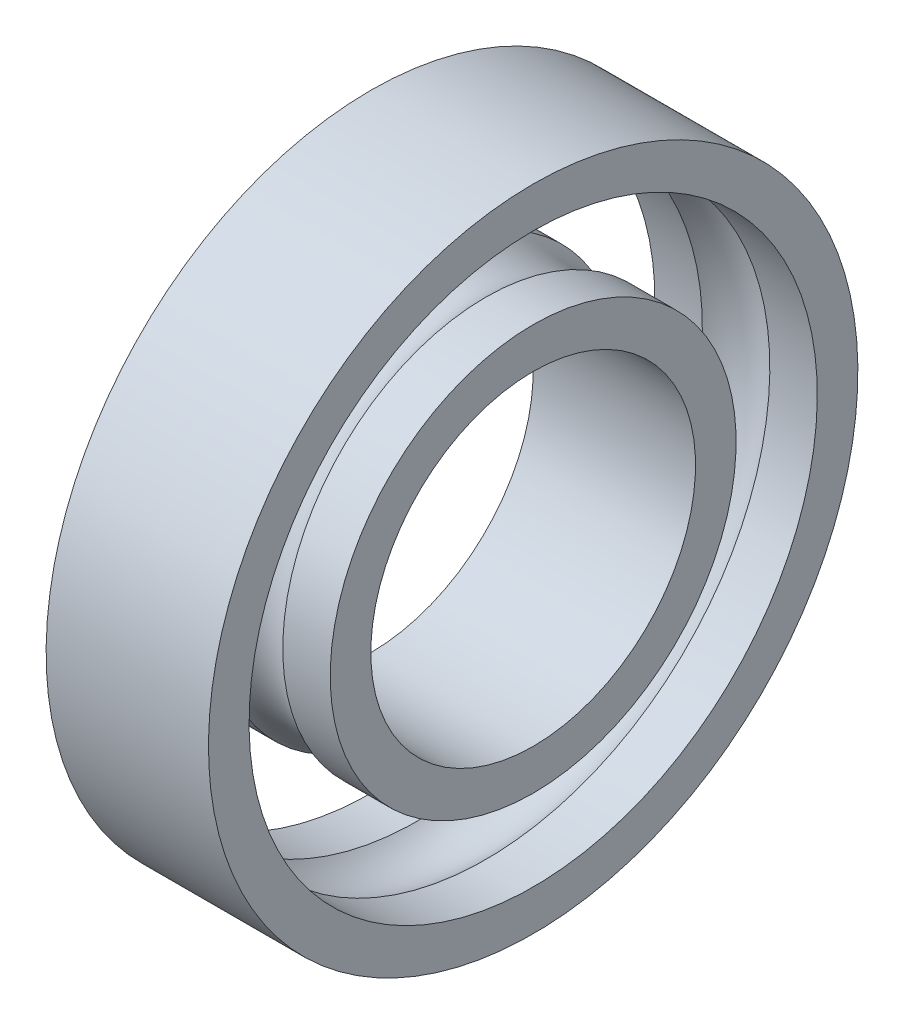
SolidWorks part; units mm, degrees
ref_plane "Front Plane" through (0, 0, 0) normal (0, 0, 1) x (1, 0, 0)
ref_plane "Top Plane" through (0, 0, 0) normal (0, 1, 0) x (1, 0, 0)
ref_plane "Right Plane" through (0, 0, 0) normal (1, 0, 0) x (0, 0, -1)
sketch "Sketch1" plane through (0, 0, 0) normal (0, 0, 1) x (1, 0, 0)
  line L0 (-10, 35) -> (-4.1533, 35)
  line L1 (-10, 20) -> (10, 20)
  line L2 (-10, 20) -> (-10, 25)
  line L3 (-10, 40) -> (10, 40)
  line L4 (10, 20) -> (10, 25)
  line L5 (-10, 20) -> (10, 40) construction
  line L6 (-10, 40) -> (10, 20) construction
  line L7 (-10, 25) -> (-4.1533, 25)
  line L8 (4.1533, 25) -> (10, 25)
  line L9 (4.1533, 35) -> (10, 35)
  line L10 (-10, 35) -> (-10, 40)
  line L11 (10, 35) -> (10, 40)
  arc A0 (-4.1533, 25) -> (4.1533, 25) centre (0, 30) ccw
  arc A1 (4.1533, 35) -> (-4.1533, 35) centre (0, 30) ccw
  point P0 (0, 30)
  dimension "D2" = 13
  dimension "D1" = 20
  dimension "D3" = 20
  dimension "D4" = 20
  dimension "D5" = 5
  dimension "D6" = 5
sketch "Sketch5" plane through (0, 0, 0) normal (1, 0, 0) x (0, 0, -1)
  circle A0 centre (0, 0) radius 30
sweep "Sweep1" add profiles "Sketch1" path "Sketch5"
